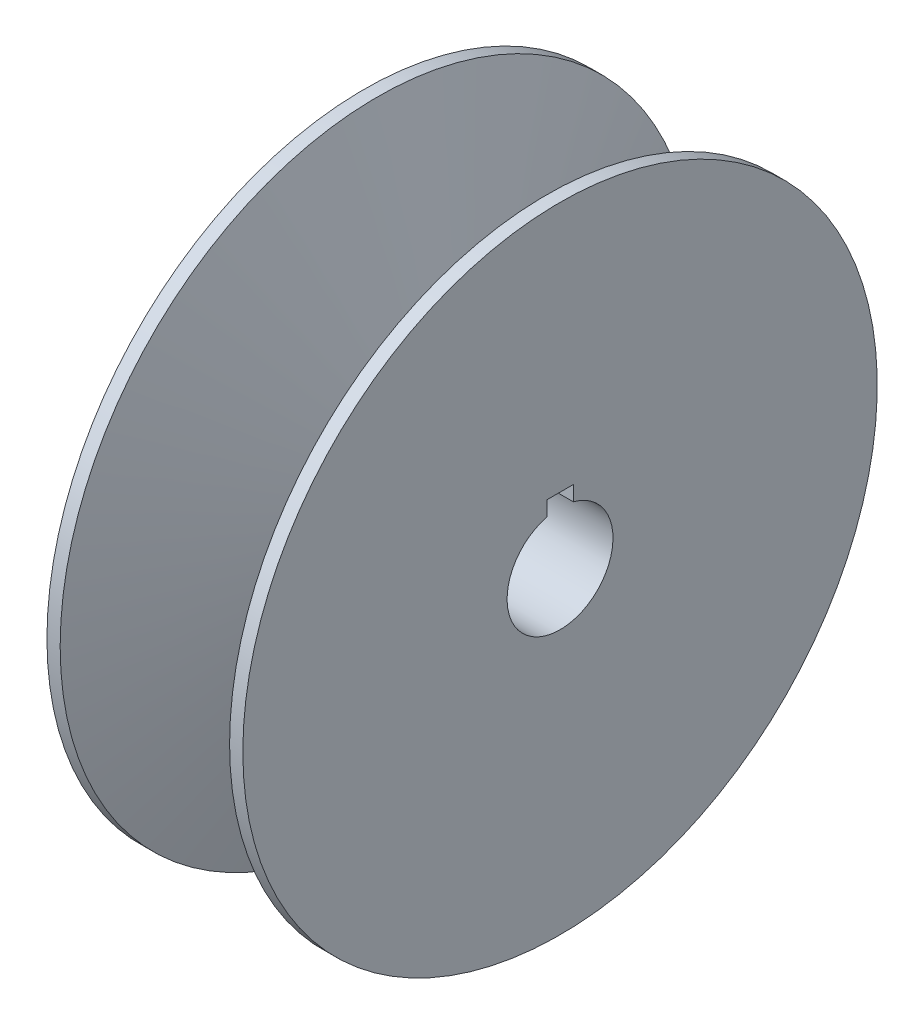
SolidWorks part; units mm, degrees
material "Plain Carbon Steel"
ref_plane "Front Plane" through (0, 0, 0) normal (0, 0, 1) x (1, 0, 0)
ref_plane "Top Plane" through (0, 0, 0) normal (0, 1, 0) x (1, 0, 0)
ref_plane "Right Plane" through (0, 0, 0) normal (1, 0, 0) x (0, 0, -1)
sketch "Sketch1" plane through (0, 0, 0) normal (0, 0, 1) x (1, 0, 0)
  line L0 (0, 0) -> (40.64, 0) construction
  line L1 (0, 0) -> (0, 76.0921) construction
  line L2 (40.64, 0) -> (40.64, 76.0921) construction
  line L3 (0, 76.0921) -> (40.64, 76.0921) construction
  line L4 (20.32, 76.0921) -> (20.32, 8.9982) construction
  line L5 (40.64, 6.35) -> (-40.64, 6.35) construction
  line L6 (0, 76.0921) -> (18.6267, 12.7)
  line L7 (40.64, 76.0921) -> (22.0133, 12.7)
  line L8 (13.2385, 31.0377) -> (27.4015, 31.0377)
  line L9 (0, 76.0921) -> (0, 6.35)
  line L10 (0, 6.35) -> (22.0133, 6.35)
  line L11 (22.0133, 12.7) -> (40.64, 12.7) construction
  line L12 (22.0133, 6.35) -> (40.64, 6.35)
  line L13 (40.64, 6.35) -> (40.64, 76.0921)
  line L14 (0, 76.0921) -> (-3.175, 76.0921)
  line L15 (-3.175, 76.0921) -> (-3.175, 6.35)
  line L16 (-3.175, 6.35) -> (0, 6.35)
  line L18 (40.64, 76.0921) -> (43.815, 76.0921)
  line L19 (40.64, 76.0921) -> (40.64, 6.35)
  line L20 (40.64, 6.35) -> (43.815, 6.35)
  line L21 (43.815, 76.0921) -> (43.815, 6.35)
  dimension "D1" = 3.175
  dimension "D2" = 40.64
  dimension "D3" = 76.0921
  dimension "D4" = 3.175
  dimension "D5" = 6.35
revolve "Revolve1" add sketch "Sketch1" angle 360 about L0
sketch "Sketch2" plane through (43.815, 0, 0) normal (1, 0, 0) x (0, 0, -1)
  line L0 (0, 0) -> (0, 12.7) construction
  line L2 (3.175, 9.525) -> (-3.175, 9.525)
  line L3 (3.175, 9.525) -> (3.175, 15.875)
  line L4 (3.175, 15.875) -> (-3.175, 15.875)
  line L5 (-3.175, 9.525) -> (-3.175, 15.875)
  line L6 (3.175, 9.525) -> (-3.175, 15.875) construction
  line L7 (3.175, 15.875) -> (-3.175, 9.525) construction
  circle A0 centre (0, 0) radius 12.7
  dimension "D1" = 25.4
  dimension "D2" = 6.35
  dimension "D3" = 6.35
extrude "Cut-Extrude1" cut sketch "Sketch2" against normal blind 108.204 and the other way blind 25.146
ref_plane "Plane1" through (20.32, 0, 0) normal (-1, 0, 0) x (0, 0, 1)
